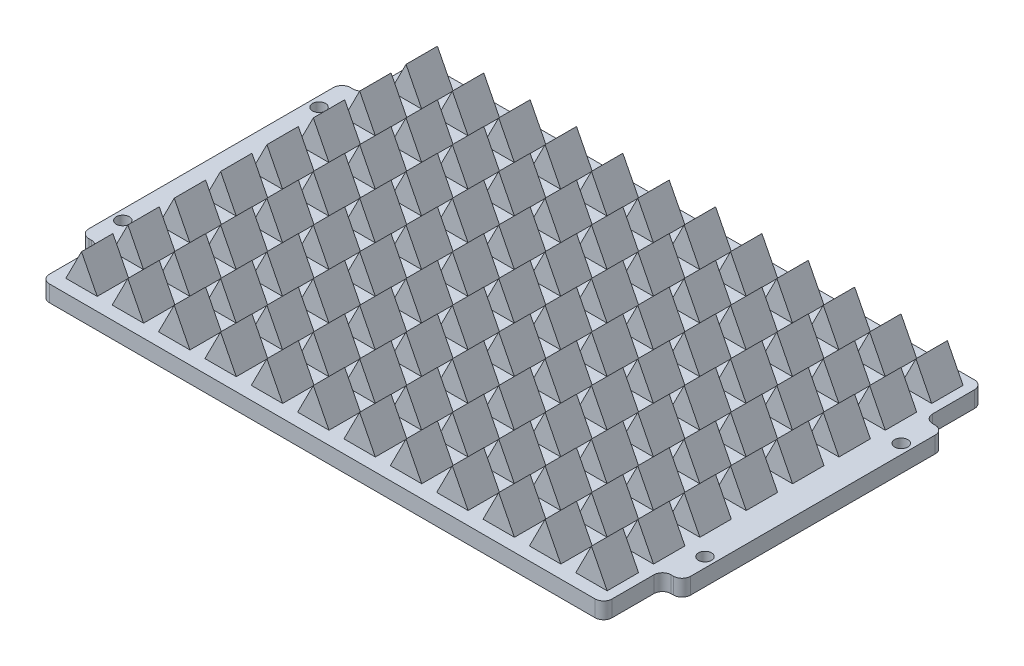
SolidWorks part; units mm, degrees
ref_plane "Front Plane" through (0, 0, 0) normal (0, 0, 1) x (1, 0, 0)
ref_plane "Top Plane" through (0, 0, 0) normal (0, 1, 0) x (1, 0, 0)
ref_plane "Right Plane" through (0, 0, 0) normal (1, 0, 0) x (0, 0, -1)
sketch "Sketch1" plane through (0, 0, 0) normal (0, 1, 0) x (1, 0, 0)
  line L1 (-54.61, -36.83) -> (54.61, -36.83)
  line L2 (-54.61, -36.83) -> (-54.61, 36.83)
  line L3 (-54.61, 36.83) -> (54.61, 36.83)
  line L4 (54.61, -36.83) -> (54.61, 36.83)
  line L5 (-54.61, -36.83) -> (54.61, 36.83) construction
  line L6 (-54.61, 36.83) -> (54.61, -36.83) construction
  point P0 (0, 0)
  dimension "D1" = 109.22
  dimension "D2" = 73.66
extrude "Boss-Extrude1" add sketch "Sketch1" against normal blind 3.175
ref_plane "Plane1" through (0, 0, -31.75) normal (0, 0, 1) x (1, 0, 0)
sketch "Sketch2" plane through (0, 0, -31.75) normal (0, 0, 1) x (1, 0, 0)
  line L0 (-52.324, 0) -> (-49.276, 6)
  line L3 (-49.276, 0) -> (-52.324, 0)
  line L4 (-49.276, 6) -> (-49.276, 0) construction
  line L5 (-49.276, 6) -> (-46.228, 0)
  line L6 (-54.61, 0) -> (54.61, 0) construction
  line L7 (-46.228, 0) -> (-49.276, 0)
  point P5 (-50.8, 0)
  dimension "D1" = 3.048
  dimension "D2" = 6
  dimension "D3" = 50.8
extrude "Boss-Extrude3" add sketch "Sketch2" along normal mid plane 6.096
pattern_linear "LPattern1" count 12 spacing 9 along (1, 0, 0) count 8 spacing 9 along (0, 0, 1) of "Boss-Extrude3"
sketch "Sketch3" plane through (0, 0, 0) normal (0, 1, 0) x (1, 0, 0)
  line L0 (-54.61, 36.83) -> (-54.61, -36.83) construction
  line L1 (-54.61, 25.4) -> (-58.42, 25.4)
  line L2 (-54.61, 25.4) -> (-54.61, -25.4)
  line L3 (-54.61, -25.4) -> (-58.42, -25.4)
  line L4 (-58.42, 25.4) -> (-58.42, -25.4)
  line L5 (0, 0) -> (0, 36.83) construction
  line L6 (54.61, 36.83) -> (-54.61, 36.83) construction
  line L7 (58.42, 25.4) -> (58.42, -25.4)
  line L8 (54.61, -25.4) -> (58.42, -25.4)
  line L9 (54.61, 25.4) -> (54.61, -25.4)
  line L10 (54.61, 25.4) -> (58.42, 25.4)
  circle A0 centre (-56.515, 19.05) radius 1.27
  circle A1 centre (-56.515, -19.05) radius 1.27
  circle A2 centre (56.515, -19.05) radius 1.27
  circle A3 centre (56.515, 19.05) radius 1.27
  point P6 (-58.42, 0)
  point P11 (-56.515, 25.4)
  dimension "D3" = 2.54
  dimension "D1" = 3.81
  dimension "D2" = 50.8
  dimension "D4" = 19.05
  dimension "D5" = 2
extrude "Boss-Extrude2" add sketch "Sketch3" against normal blind 3.175
fillet "Fillet1" radius 1.651 12 edges at (54.61, -1.5875, -36.83) (54.61, -1.5875, -25.4) (58.42, -1.5875, -25.4) (58.42, -1.5875, 25.4) (54.61, -1.5875, 25.4) (54.61, -1.5875, 36.83) (-54.61, -1.5875, 36.83) (-54.61, -1.5875, 25.4) (-58.42, -1.5875, 25.4) (-58.42, -1.5875, -25.4) (-54.61, -1.5875, -25.4) (-54.61, -1.5875, -36.83)
